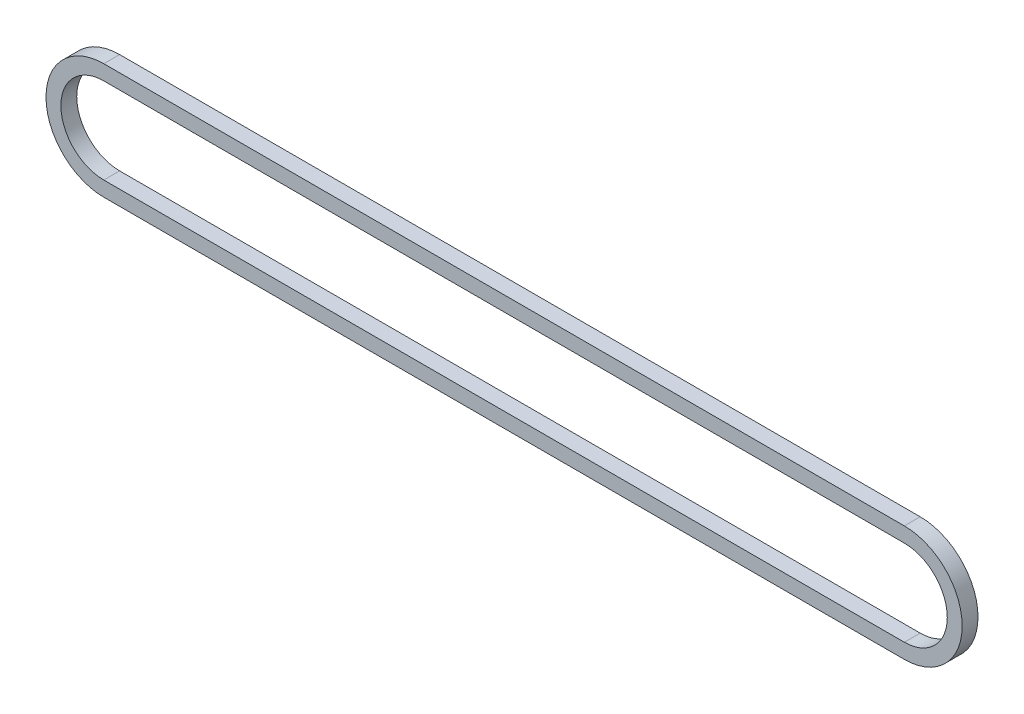
SolidWorks part; units mm, degrees
material "AISI 1020"
ref_plane "前视基准面" through (0, 0, 0) normal (0, 0, 1) x (1, 0, 0)
ref_plane "上视基准面" through (0, 0, 0) normal (0, 1, 0) x (1, 0, 0)
ref_plane "右视基准面" through (0, 0, 0) normal (1, 0, 0) x (0, 0, -1)
sketch "草图1" plane through (0, 0, 0) normal (0, 0, 1) x (1, 0, 0)
  line L0 (-161.275, 0) -> (161.275, 0) construction
  line L1 (-161.275, 23.295) -> (161.275, 23.295)
  line L2 (-161.275, -23.295) -> (161.275, -23.295)
  line L3 (-161.275, 17.295) -> (161.275, 17.295)
  line L4 (-161.275, -17.295) -> (161.275, -17.295)
  circle A0 centre (-161.275, 0) radius 20.295 construction
  circle A1 centre (161.275, 0) radius 20.295 construction
  arc A2 (-161.275, 23.295) -> (-161.275, -23.295) centre (-161.275, 0) ccw
  arc A3 (161.275, -23.295) -> (161.275, 23.295) centre (161.275, 0) ccw
  arc A4 (-161.275, 17.295) -> (-161.275, -17.295) centre (-161.275, 0) ccw
  arc A5 (161.275, -17.295) -> (161.275, 17.295) centre (161.275, 0) ccw
  circle A6 centre (-161.275, 0) radius 23.295 construction
  circle A7 centre (161.275, 0) radius 23.295 construction
  circle A8 centre (-161.275, 0) radius 17.295 construction
  circle A9 centre (161.275, 0) radius 17.295 construction
  point P4 (0, 0)
  dimension "D2" = 40.59
  dimension "D1" = 322.55
  dimension "D3" = 3
  dimension "D4" = 3
  dimension "D5" = 3
  dimension "D6" = 3
extrude "凸台-拉伸1" add sketch "草图1" along normal mid plane 6.38
